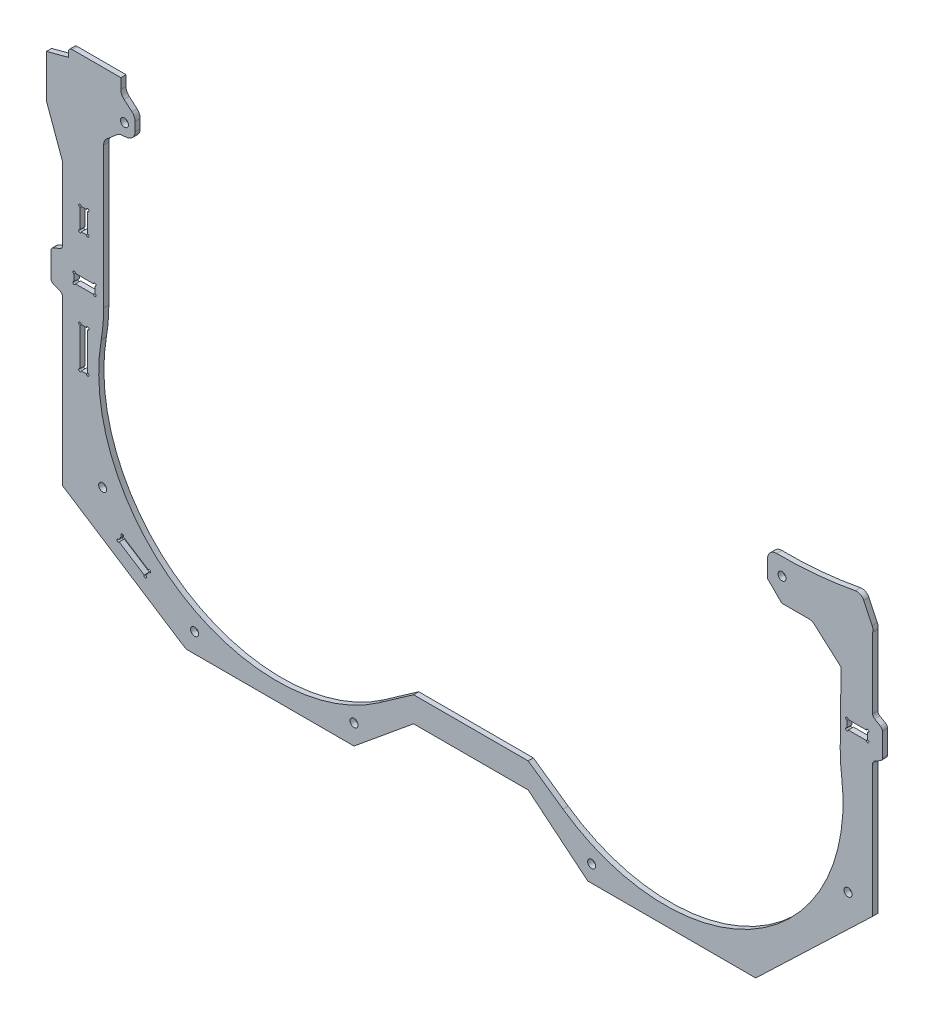
SolidWorks part; units mm, degrees
material "PPS"
ref_plane "前视基准面" through (0, 0, 0) normal (0, 0, 1) x (1, 0, 0)
ref_plane "上视基准面" through (0, 0, 0) normal (0, 1, 0) x (1, 0, 0)
ref_plane "右视基准面" through (0, 0, 0) normal (1, 0, 0) x (0, 0, -1)
sketch "草图1" plane through (0, 0, 0) normal (0, 0, 1) x (1, 0, 0)
  line L0 (-816.4831, 0) -> (39952.7477, 0) construction
  line L1 (0, 10.8762) -> (0, -592.6628) construction
  line L2 (0, 0) -> (206.9686, -284.8678) construction
  line L9 (155.1848, -135.6229) -> (110.024, -178.8146)
  line L10 (110.024, -178.8146) -> (45.146, -178.8146)
  line L60 (-110.024, -178.8146) -> (-45.146, -178.8146)
  line L119 (-135.8935, -19.3983) -> (-141.8504, -24.5203)
  line L187 (152.75, -77.5) -> (145.75, -77.5) construction
  line L188 (152.75, -77.5) -> (152.75, -75) construction
  line L189 (145.75, -77.5) -> (145.75, -75) construction
  line L190 (152.75, -75) -> (145.75, -75) construction
  line L191 (-145.75, -75) -> (-152.75, -75) construction
  line L192 (-152.75, -75) -> (-152.75, -77.5) construction
  line L193 (-152.75, -77.5) -> (-145.75, -77.5) construction
  line L194 (-145.75, -77.5) -> (-145.75, -75) construction
  line L195 (145.25, -74.5) -> (153.25, -74.5)
  line L196 (153.25, -74.5) -> (153.25, -78)
  line L197 (153.25, -78) -> (145.25, -78)
  line L198 (145.25, -78) -> (145.25, -74.5)
  line L199 (-153.25, -78) -> (-145.25, -78)
  line L200 (-153.25, -74.5) -> (-153.25, -78)
  line L201 (-145.25, -74.5) -> (-153.25, -74.5)
  line L202 (-145.25, -78) -> (-145.25, -74.5)
  line L204 (-135.1929, -0.25) -> (-155.5041, -0.25)
  line L206 (-155.5041, -0.25) -> (-155.5041, -3.6009)
  line L207 (-155.5041, -3.6009) -> (-163.9299, -5.8429)
  line L208 (-155.5041, -3.6009) -> (-170.0041, -7.4592) construction
  line L209 (-163.9299, -5.8429) -> (-163.9299, -22.4613)
  line L210 (-163.9299, -22.4613) -> (-157.7253, -39.5836)
  line L211 (-157.7253, -39.5836) -> (-157.7253, -148.0115)
  line L212 (-157.7253, -148.0115) -> (-110.024, -178.8146)
  line L215 (114.5778, -32.685) -> (114.5778, -42.9165)
  line L216 (120.0778, -48.4165) -> (131.782, -48.4165)
  line L217 (131.782, -48.4165) -> (142.9662, -58.3127)
  line L219 (151.7709, -31.6811) -> (155.0114, -38.4796)
  line L220 (155.1848, -40.6053) -> (155.1848, -135.6229)
  line L221 (120.1823, -39.335) -> (149.4323, -39.335) construction
  line L222 (92.9352, -48.4165) -> (142.5788, -48.4165) construction
  line L223 (75, -103.2286) -> (164.6276, -103.2286) construction
  line L224 (75, -103.2286) -> (35.5666, -159.5453) construction
  line L226 (35.5666, -159.5453) -> (22.126, -150.1341)
  line L227 (22.126, -150.1341) -> (-22.126, -150.1341)
  line L228 (22.126, -159.8702) -> (-22.126, -159.8702)
  line L229 (22.126, -159.8702) -> (45.146, -178.8146)
  line L230 (-35.5666, -159.5453) -> (-22.126, -150.1341)
  line L231 (-22.126, -159.8702) -> (-45.146, -178.8146)
  line L233 (114.5778, -42.9165) -> (120.0778, -48.4165)
  line L234 (75, -103.2286) -> (142.5988, -90.7) construction
  line L235 (142.9662, -58.3127) -> (142.5988, -90.7)
  line L236 (142.5988, -90.7) -> (142.5988, -57.1472) construction
  line L238 (-141.8504, -87.1793) -> (-75, -103.2286) construction
  line L239 (-75, -103.2286) -> (-143.75, -103.2286) construction
  line L240 (-141.8504, -24.5203) -> (-141.8504, -87.1793)
  line L241 (-135.1929, -0.25) -> (-135.1929, -5.85)
  line L242 (-135.1929, -5.85) -> (-129.7197, -10.5767)
  line L243 (-129.7197, -10.5767) -> (-129.7197, -18.7984)
  line L244 (-129.7197, -18.7984) -> (-135.8935, -19.3983)
  circle A76 centre (75, -103.2286) radius 68.75 construction
  circle A78 centre (-133.8062, -14.6009) radius 1.55
  arc A79 (155.0114, -38.4796) -> (155.1848, -40.6053) centre (152.3033, -39.7704) cw
  circle A80 centre (-75, -103.2286) radius 68.75 construction
  arc A81 (148.5011, -30.0249) -> (151.7709, -31.6811) centre (149.0628, -32.9719) cw
  arc A82 (153.902, -42.309) -> (155.0114, -38.4796) centre (152.3033, -39.7704) ccw construction
  arc A83 (148.5011, -30.0249) -> (114.5778, -32.685) centre (119.5082, 122.0773) cw
  arc A84 (97.7907, -31.2329) -> (148.5011, -30.0249) centre (119.5082, 122.0773) ccw construction
  circle A85 centre (149.4323, -39.335) radius 1.55 construction
  circle A86 centre (120.1823, -39.335) radius 1.55
  arc A87 (35.5666, -159.5453) -> (143.75, -103.2286) centre (75, -103.2286) ccw
  arc A88 (-35.5666, -159.5453) -> (-143.75, -103.2286) centre (-75, -103.2286) cw
  arc A89 (142.5988, -90.7) -> (143.75, -103.2286) centre (75, -103.2286) cw
  arc A91 (-143.75, -103.2286) -> (-141.8504, -87.1793) centre (-75, -103.2286) cw
  point P10 (149.25, -75)
  point P29 (0, -150.1341)
  point P32 (0, 0)
  point P38 (153.25, -76.25)
  point P92 (0, -159.8702)
  dimension "D1" = 36
  dimension "D2" = 75
  dimension "D3" = 137.5
  dimension "D6" = 75
  dimension "D7" = 149.25
  dimension "D15" = 125
  dimension "D14" = 3.1
  dimension "D4" = 2.5
  dimension "D5" = 7
  dimension "D8" = 7
  dimension "D9" = 0.5
  dimension "D10" = 0.5
  dimension "D11" = 0.5
  dimension "D12" = 0.5
  dimension "D13" = 29.25
  dimension "D16" = 10.5
  dimension "D17" = 0.65
  dimension "D18" = 13.5
  dimension "D19" = 0.25
extrude "凸台-拉伸1" add sketch "草图1" along normal blind 2
sketch "草图2" plane through (0, 0, 0) normal (0, 0, 1) x (1, 0, 0)
  line L0 (155.1848, -68.75) -> (158.9348, -70.9151)
  line L1 (155.1848, -135.6229) -> (155.1848, -40.6053) construction
  line L2 (158.9348, -70.9151) -> (158.9348, -81.5849)
  line L3 (158.9348, -81.5849) -> (155.1848, -83.75)
  line L4 (155.1848, -83.75) -> (155.1848, -68.75)
  line L5 (153.25, -76.25) -> (184.2947, -76.25) construction
  line L6 (153.25, -78) -> (153.25, -74.5) construction
  line L7 (-153.25, -76.25) -> (-171.2105, -76.25) construction
  line L8 (-153.25, -74.5) -> (-153.25, -78) construction
  line L9 (-157.7253, -68.75) -> (-157.7253, -83.75)
  line L10 (-157.7253, -39.5836) -> (-157.7253, -148.0115) construction
  line L11 (-157.7253, -83.75) -> (-162.2253, -81.886)
  line L12 (-162.2253, -81.886) -> (-162.2253, -70.614)
  line L13 (-162.2253, -70.614) -> (-157.7253, -68.75)
  dimension "D1" = 3.75
  dimension "D2" = 7.5
  dimension "D3" = 60
  dimension "D4" = 67.5
  dimension "D5" = 4.5
extrude "凸台-拉伸2" add sketch "草图2" against normal up to surface (2 mm away) from surface at 2 up to face at (-132.2562, -14.6009, 0) starting at face at (149.25, -76.25, 2)
fillet "圆角1" radius 66.25 2 edges at (-141.8504, -87.1793, 1) (142.5988, -90.7, 1)
fillet "圆角4" radius 1.5 9 edges at (155.1848, -68.75, 1) (158.9348, -70.9151, 1) (155.1848, -83.75, 1) (158.9348, -81.5849, 1) (-155.5041, -0.25, 1) (-157.7253, -68.75, 1) (-162.2253, -70.614, 1) (-162.2253, -81.886, 1) (-157.7253, -83.75, 1)
sketch "板状设备接口" plane through (0, 0, 2) normal (0, 0, 1) x (1, 0, 0)
  line L0 (-151, -90.5) -> (-148, -90.5)
  line L1 (-148, -90.5) -> (-148, -106)
  line L2 (-148, -106) -> (-151, -106)
  line L3 (-151, -106) -> (-151, -90.5)
  line L4 (-148, -77.5) -> (-148, -75) construction
  line L5 (-151, -75) -> (-151, -77.5) construction
  line L6 (-151, -51) -> (-148, -51)
  line L7 (-148, -51) -> (-148, -59.5)
  line L8 (-148, -59.5) -> (-151, -59.5)
  line L9 (-151, -59.5) -> (-151, -51)
  line L10 (-145.25, -74.5) -> (-153.25, -74.5) construction
  line L11 (-153.25, -78) -> (-145.25, -78) construction
  line L12 (-134.6497, -153.092) -> (-124.1488, -159.8729)
  line L13 (-124.1488, -159.8729) -> (-125.7762, -162.3931)
  line L14 (-125.7762, -162.3931) -> (-136.2771, -155.6122)
  line L15 (-136.2771, -155.6122) -> (-134.6497, -153.092)
  line L21 (-157.7253, -148.0115) -> (-110.024, -178.8146) construction
  line L22 (-131.0266, -159.0026) -> (-133.8746, -163.413) construction
  dimension "D1" = 15
  dimension "D2" = 8.5
  dimension "D3" = 12.5
  dimension "D4" = 15.5
  dimension "D5" = 5.25
  dimension "D6" = 12.5
  dimension "D7" = 3
extrude "设备接口" cut sketch "板状设备接口" against normal through all
sketch "草图4" plane through (0, 0, 0) normal (0, 0, 1) x (1, 0, 0)
  line L0 (-157.7253, -84.7523) -> (-157.7253, -148.0115) construction
  line L1 (-110.024, -178.8146) -> (-45.146, -178.8146) construction
  line L2 (155.1848, -135.6229) -> (155.1848, -84.616) construction
  line L3 (-45.146, -171.0646) -> (-45.146, -178.8146) construction
  line L4 (45.146, -178.8146) -> (110.024, -178.8146) construction
  circle A0 centre (-142.2253, -140.8215) radius 1.55
  circle A1 centre (-45.146, -171.0646) radius 1.55
  circle A2 centre (-106.713, -171.3146) radius 1.55
  circle A3 centre (46.656, -172.3146) radius 1.55
  circle A4 centre (145.6848, -132.301) radius 1.55
  dimension "D5" = 3.1
  dimension "D1" = 15.5
  dimension "D2" = 7.5
  dimension "D3" = 7.75
  dimension "D4" = 9.5
  dimension "D6" = 6.5
extrude "切除-拉伸3" cut sketch "草图4" along normal through all
fillet "圆角5" radius 3.5 7 edges at (131.782, -48.4165, 1) (114.5778, -32.685, 1) (-141.8504, -24.5203, 1) (-129.7197, -10.5767, 1) (-135.1929, -5.85, 1) (-135.8935, -19.3983, 1) (-129.7197, -18.7984, 1)
sketch "过切除" plane through (0, 0, 0) normal (0, 0, 1) x (1, 0, 0)
  circle A0 centre (-151, -51) radius 0.5
  circle A1 centre (-148, -51) radius 0.5
  circle A2 centre (-151, -59.5) radius 0.5
  circle A3 centre (-148, -59.5) radius 0.5
  circle A4 centre (-153.25, -74.5) radius 0.5
  circle A5 centre (-145.25, -74.5) radius 0.5
  circle A6 centre (-145.25, -78) radius 0.5
  circle A7 centre (-153.25, -78) radius 0.5
  circle A8 centre (-151, -90.5) radius 0.5
  circle A9 centre (-148, -90.5) radius 0.5
  circle A10 centre (-151, -106) radius 0.5
  circle A11 centre (-148, -106) radius 0.5
  circle A12 centre (-134.6497, -153.092) radius 0.5
  circle A13 centre (-136.2771, -155.6122) radius 0.5
  circle A14 centre (-124.1488, -159.8729) radius 0.5
  circle A15 centre (-125.7762, -162.3931) radius 0.5
  circle A16 centre (145.25, -74.5) radius 0.5
  circle A17 centre (153.25, -74.5) radius 0.5
  circle A18 centre (153.25, -78) radius 0.5
  circle A19 centre (145.25, -78) radius 0.5
  dimension "D1" = 1
extrude "这个是因为刀的限制不能切直角" cut sketch "过切除" along normal through all
